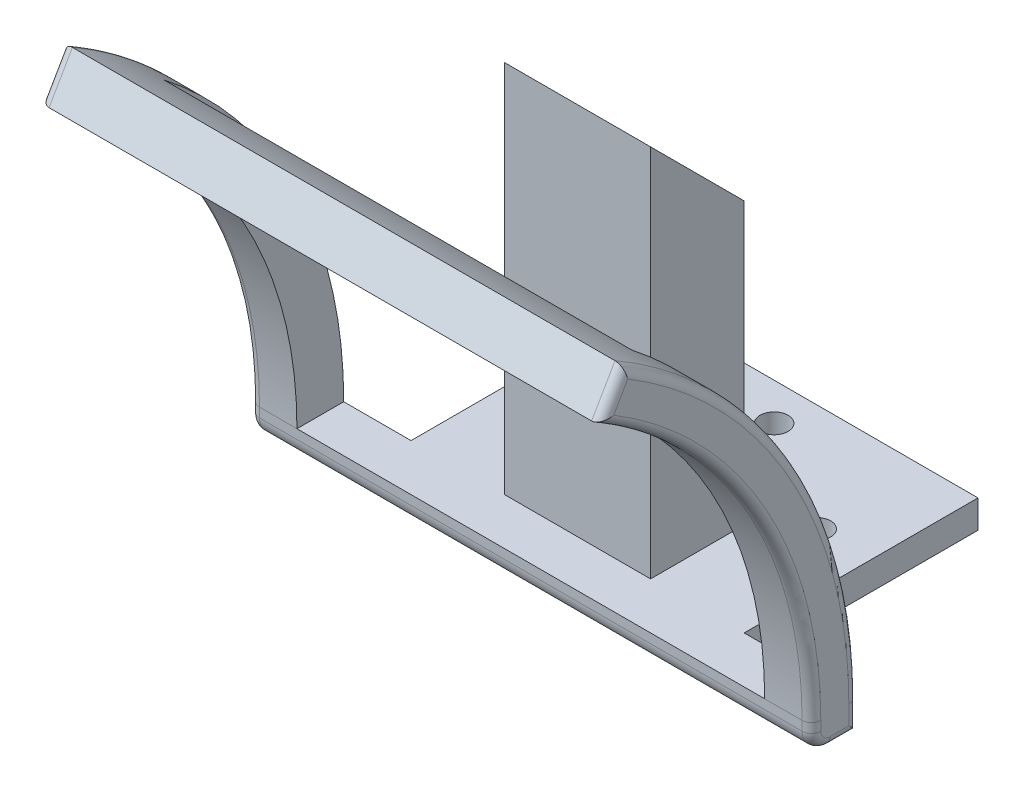
SolidWorks part; units mm, degrees
ref_plane "Front Plane" through (0, 0, 0) normal (0, 0, 1) x (1, 0, 0)
ref_plane "Top Plane" through (0, 0, 0) normal (0, 1, 0) x (1, 0, 0)
ref_plane "Right Plane" through (0, 0, 0) normal (1, 0, 0) x (0, 0, -1)
sketch "Sketch1" plane through (0, 0, 0) normal (0, 1, 0) x (1, 0, 0)
  line L0 (-8.4368, 20.25) -> (-8.4368, -4.75) construction
  line L1 (-26.2418, 20.25) -> (9.3682, 20.25)
  line L2 (-26.2418, 20.25) -> (-26.2418, -4.75)
  line L3 (-26.2418, -4.75) -> (9.3682, -4.75)
  line L4 (9.3682, 20.25) -> (9.3682, -4.75)
  line L5 (-38.4368, -4.75) -> (21.5632, -4.75)
  line L6 (-38.4368, -4.75) -> (-38.4368, -9.75)
  line L7 (-38.4368, -9.75) -> (21.5632, -9.75)
  line L8 (21.5632, -4.75) -> (21.5632, -9.75)
  point P10 (-8.4368, -4.75)
  dimension "D1" = 25
  dimension "D2" = 35.61
  dimension "D3" = 60
  dimension "D4" = 5
extrude "Boss-Extrude1" add sketch "Sketch1" along normal blind 3 contours L8 L5 L3 L6 L7 | L1 L0 L5 L4 | L0 L1 L2 L3
fillet "Fillet1" radius 2 1 edges at (-8.4368, 0, 9.75)
ref_plane "Plane1" through (21.5632, 0, 0) normal (1, 0, 0) x (0, 0, -1)
sketch "Sketch2" plane through (21.5632, 0, 0) normal (1, 0, 0) x (0, 0, -1)
  line L0 (-9.75, 3) -> (-39.75, 3) construction
  line L1 (-39.75, 3) -> (-54.75, 3) construction
  line L2 (-29.75, 46.3013) -> (-32.25, 41.9711)
  line L3 (-9.75, 3) -> (-4.75, 3)
  circle A0 centre (-54.75, 3) radius 15 construction
  arc A1 (-9.75, 3) -> (-32.25, 41.9711) centre (-54.75, 3) ccw
  arc A2 (-4.75, 3) -> (-29.75, 46.3013) centre (-54.75, 3) ccw
  dimension "D3" = 30
  dimension "D1" = 30
  dimension "D2" = 15
extrude "Boss-Extrude3" add sketch "Sketch2" against normal blind 5
ref_plane "Plane2" through (-8.4368, 0, 0) normal (1, 0, 0) x (0, 0, -1)
mirror "Mirror3" about plane through (-8.4368, 0, 0) normal (1, 0, 0) of "Boss-Extrude3"
sketch "Sketch3" plane through (0, 0, 0) normal (0, -1, 0) x (1, 0, 0)
  circle A0 centre (-20.4847, -8.75) radius 1.5
  circle A1 centre (-8.4349, -16.25) radius 1.5
  circle A2 centre (3.6149, -8.75) radius 1.5
  dimension "D1" = 3
extrude "Cut-Extrude1" cut sketch "Sketch3" against normal blind 5
sketch "Sketch7" plane through (0, 3, 0) normal (0, 1, 0) x (1, 0, 0)
  line L0 (-26.2418, 20.25) -> (-26.2418, -4.75) construction
  line L1 (-16.2418, 5.25) -> (-0.6318, 5.25)
  line L2 (-16.2418, 5.25) -> (-16.2418, -4.75)
  line L3 (-16.2418, -4.75) -> (-0.6318, -4.75)
  line L4 (-0.6318, 5.25) -> (-0.6318, -4.75)
  line L5 (9.3682, 20.25) -> (9.3682, -4.75) construction
  line L6 (-38.4368, -9.75) -> (21.5632, -9.75) construction
  dimension "D1" = 10
  dimension "D2" = 10
  dimension "D3" = 5
  dimension "D4" = 10
extrude "Boss-Extrude4" add sketch "Sketch7" along normal blind 30
sketch "Sketch8" plane through (-16.2418, 0, 0) normal (-1, 0, 0) x (0, 0, 1)
  line L0 (-5.25, 33) -> (4.75, 43)
  line L1 (4.75, 33) -> (4.75, 43)
  line L2 (-5.25, 33) -> (4.75, 33) construction
  line L3 (-5.25, 33) -> (4.75, 33)
  dimension "D1" = 45
extrude "Boss-Extrude5" add sketch "Sketch8" against normal up to surface (15.61 mm away) up to face at (-0.6318, 18, -0.25)
sketch "Sketch9" plane through (0, 19.125, -19.125) normal (0, 0.7071, -0.7071) x (1, 0, 0)
  line L0 (-16.2418, -26.6933) -> (-0.6318, -26.6933) construction
  line L1 (-16.2418, -33.7643) -> (-16.2418, -19.6222) construction
  line L2 (-0.6318, -19.6222) -> (-0.6318, -33.7643) construction
  line L3 (-8.4368, -19.6222) -> (-8.4368, -33.7643) construction
  line L4 (-0.6318, -19.6222) -> (-16.2418, -19.6222) construction
  line L5 (-0.6318, -33.7643) -> (-16.2418, -33.7643) construction
  circle A0 centre (-11.4368, -26.6933) radius 1.5
  circle A1 centre (-5.4368, -26.6933) radius 1.5
  dimension "D1" = 3
  dimension "D2" = 3
  dimension "D3" = 6
  dimension "D4" = 3
extrude "Cut-Extrude2" cut sketch "Sketch9" against normal blind 5
sketch "Sketch10" plane through (-33.4368, 0, 0) normal (1, 0, 0) x (0, 0, -1)
  line L0 (-23.9669, 42.4005) -> (-27.0452, 38.4605)
  line L2 (-9.75, 3) -> (-4.75, 3)
  line L3 (-29.75, 46.3013) -> (-32.25, 41.9711)
  line L4 (-9.75, 3) -> (-4.75, 3)
  line L5 (-29.75, 46.3013) -> (-32.25, 41.9711)
  arc A2 (-9.75, 3) -> (-32.25, 41.9711) centre (-54.75, 3) ccw
  arc A3 (-4.75, 3) -> (-29.75, 46.3013) centre (-54.75, 3) ccw
  arc A4 (-9.75, 3) -> (-32.25, 41.9711) centre (-54.75, 3) ccw
  arc A5 (-4.75, 3) -> (-29.75, 46.3013) centre (-54.75, 3) ccw
  arc M6 (-32.25, 41.9711) -> (-9.75, 3) centre (-54.75, 3) cw
  arc M8 (-4.75, 3) -> (-29.75, 46.3013) centre (-54.75, 3) ccw
  line M9 (-29.75, 46.3013) -> (-32.25, 41.9711)
  dimension "D2" = 8
  dimension "D1" = 0
extrude "Boss-Extrude6" add sketch "Sketch10" along normal up to surface (50 mm away) contours L0 M8 M9 M6 up to face at (16.5632, 25.1591, 16.3694)
fillet "Fillet2" radius 1 14 edges at (-38.4368, 0, 6.25) (21.5632, 0, 6.25) (21.5632, 2.5, 9.75) (-38.4368, 2.5, 9.75) (-38.4368, 1.5, 4.75) (21.5632, 1.5, 4.75) (21.5632, 0.5858, 9.1642) (-38.4368, 0.5858, 9.1642) (21.5632, 25.5, 15.7789) (21.5632, 28, 11.4487) (21.5632, 44.1362, 31) (-38.4368, 25.5, 15.7789) (-38.4368, 28, 11.4487) (-38.4368, 44.1362, 31)
